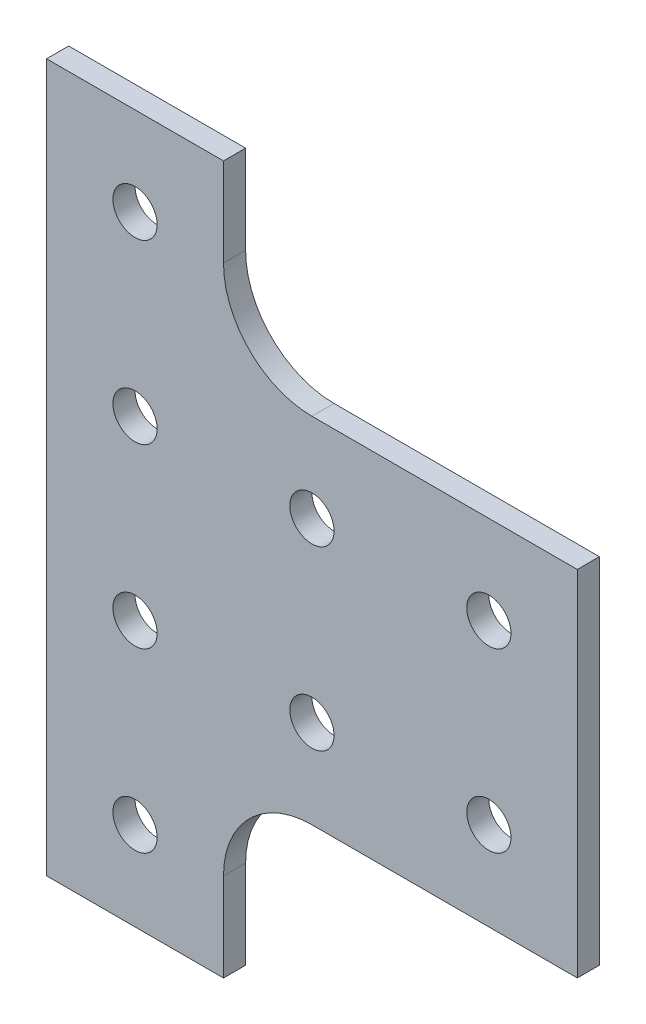
SolidWorks part; units mm, degrees
ref_plane "Front Plane" through (0, 0, 0) normal (0, 0, 1) x (1, 0, 0)
ref_plane "Top Plane" through (0, 0, 0) normal (0, 1, 0) x (1, 0, 0)
ref_plane "Right Plane" through (0, 0, 0) normal (1, 0, 0) x (0, 0, -1)
sketch "Sketch1" plane through (0, 0, 0) normal (0, 0, 1) x (1, 0, 0)
  line L0 (0, 0) -> (0, 101.6)
  line L1 (0, 101.6) -> (25.4, 101.6)
  line L2 (25.4, 101.6) -> (25.4, 76.2)
  line L3 (25.4, 76.2) -> (76.2, 76.2)
  line L4 (76.2, 76.2) -> (76.2, 25.4)
  line L5 (76.2, 25.4) -> (25.4, 25.4)
  line L6 (25.4, 25.4) -> (25.4, 0)
  line L7 (25.4, 0) -> (0, 0)
  line L8 (12.7, 88.9) -> (12.7, 101.6) construction
  line L9 (12.7, 88.9) -> (25.4, 88.9) construction
  line L10 (12.7, 88.9) -> (12.7, 63.5) construction
  line L11 (38.1, 63.5) -> (12.7, 63.5) construction
  circle A0 centre (12.7, 88.9) radius 3.175
  circle A1 centre (12.7, 63.5) radius 3.175
  circle A2 centre (12.7, 38.1) radius 3.175
  circle A3 centre (12.7, 12.7) radius 3.175
  circle A4 centre (38.1, 63.5) radius 3.175
  circle A5 centre (38.1, 38.1) radius 3.175
  circle A6 centre (63.5, 63.5) radius 3.175
  circle A7 centre (63.5, 38.1) radius 3.175
  dimension "D4" = 6.35
  dimension "D1" = 50.8
  dimension "D2" = 25.4
  dimension "D3" = 101.6
  dimension "D6" = 25.4
  dimension "D5" = 4
  dimension "D7" = 3
extrude "Boss-Extrude1" add sketch "Sketch1" along normal blind 3.175
fillet "Fillet1" radius 12.7 2 edges at (25.4, 25.4, 1.5875) (25.4, 76.2, 1.5875)
